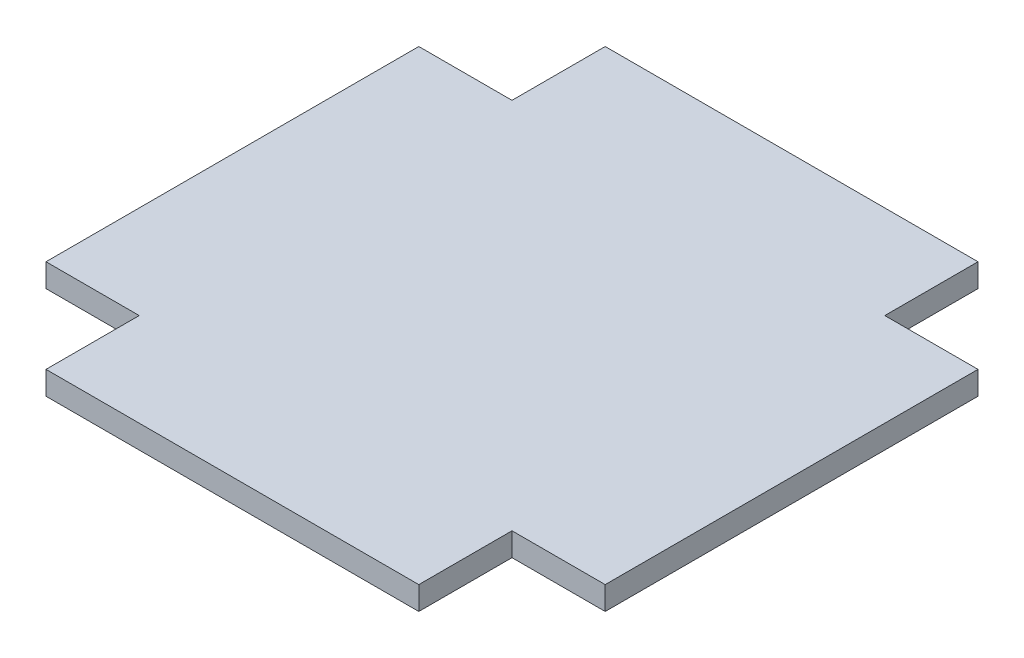
SolidWorks part; units mm, degrees
material "ABS PC"
ref_plane "Front Plane" through (0, 0, 0) normal (0, 0, 1) x (1, 0, 0)
ref_plane "Top Plane" through (0, 0, 0) normal (0, 1, 0) x (1, 0, 0)
ref_plane "Right Plane" through (0, 0, 0) normal (1, 0, 0) x (0, 0, -1)
sketch "Sketch1" plane through (0, 0, 0) normal (0, 1, 0) x (1, 0, 0)
  line L0 (-20, 30) -> (-20, 20)
  line L1 (-20, 30) -> (20, 30)
  line L2 (-30, 20) -> (-30, -20)
  line L3 (-20, -30) -> (20, -30)
  line L4 (30, 20) -> (30, -20)
  line L5 (-30, 30) -> (30, -30) construction
  line L6 (-19.6957, -53.029) -> (9.8479, 26.5145) construction
  line L7 (-20, 20) -> (-30, 20)
  line L8 (-30, -20) -> (-20, -20)
  line L9 (-20, -20) -> (-20, -30)
  line L10 (20, 30) -> (20, 20)
  line L11 (20, 20) -> (30, 20)
  line L12 (20, -30) -> (20, -20)
  line L13 (20, -20) -> (30, -20)
  point P0 (0, 0)
  dimension "D1" = 60
  dimension "D2" = 40
  dimension "D3" = 10
  dimension "D4" = 10
  dimension "D5" = 10
  dimension "D6" = 10
  dimension "D7" = 10
  dimension "D8" = 10
  dimension "D9" = 10
  dimension "D10" = 10
extrude "Boss-Extrude1" add sketch "Sketch1" along normal blind 2.5
